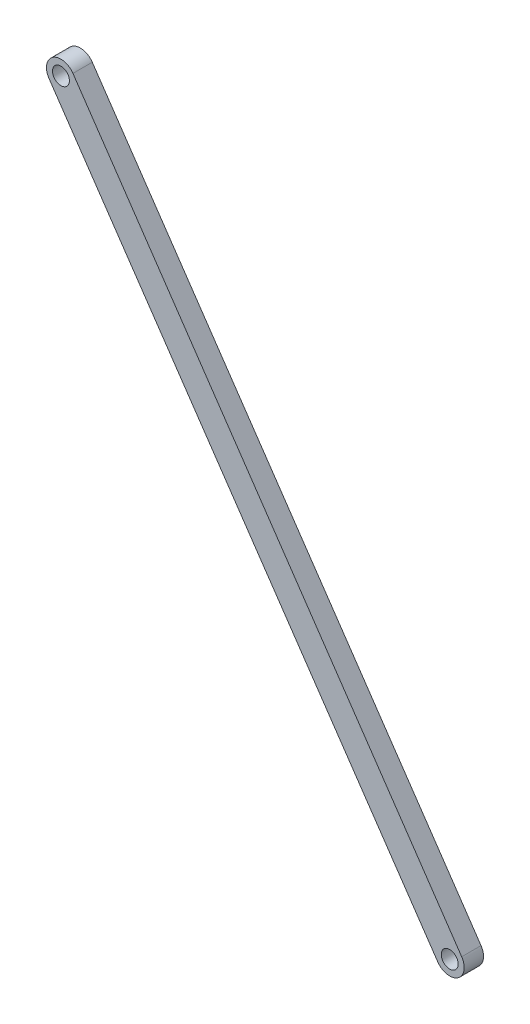
SolidWorks part; units mm, degrees
ref_plane "Front Plane" through (0, 0, 0) normal (0, 0, 1) x (1, 0, 0)
ref_plane "Top Plane" through (0, 0, 0) normal (0, 1, 0) x (1, 0, 0)
ref_plane "Right Plane" through (0, 0, 0) normal (1, 0, 0) x (0, 0, -1)
sketch "Sketch1" plane through (32.9061, 0, 0) normal (0, 0, 1) x (1, 0, 0)
  line L0 (22.809, -262.6056) -> (-57.5758, -144.6056) construction
  line L1 (20.3297, -264.2946) -> (-60.0551, -146.2946)
  line L2 (25.2884, -260.9165) -> (-55.0964, -142.9165)
  circle A2 centre (22.809, -262.6056) radius 1.75
  circle A3 centre (-57.5758, -144.6056) radius 1.6
  arc A4 (20.3297, -264.2946) -> (25.2884, -260.9165) centre (22.809, -262.6056) ccw
  arc A5 (-55.0964, -142.9165) -> (-60.0551, -146.2946) centre (-57.5758, -144.6056) ccw
  point P1 (-57.5758, -144.6056)
  point P3 (0, 0)
  point P6 (-17.3834, -203.6056)
  point P11 (0, 0)
  dimension "D1" = 3
  dimension "D2" = 3.2
  dimension "D3" = 3.5
  dimension "D4" = 118
extrude "Boss-Extrude1" add sketch "Sketch1" along normal blind 4
sketch "Sketch2" plane through (32.9061, 0, 0) normal (0, 0, -1) x (-1, 0, 0)
  circle A1 centre (57.5758, -144.6056) radius 1.75
extrude "Cut-Extrude1" cut sketch "Sketch2" against normal through all
